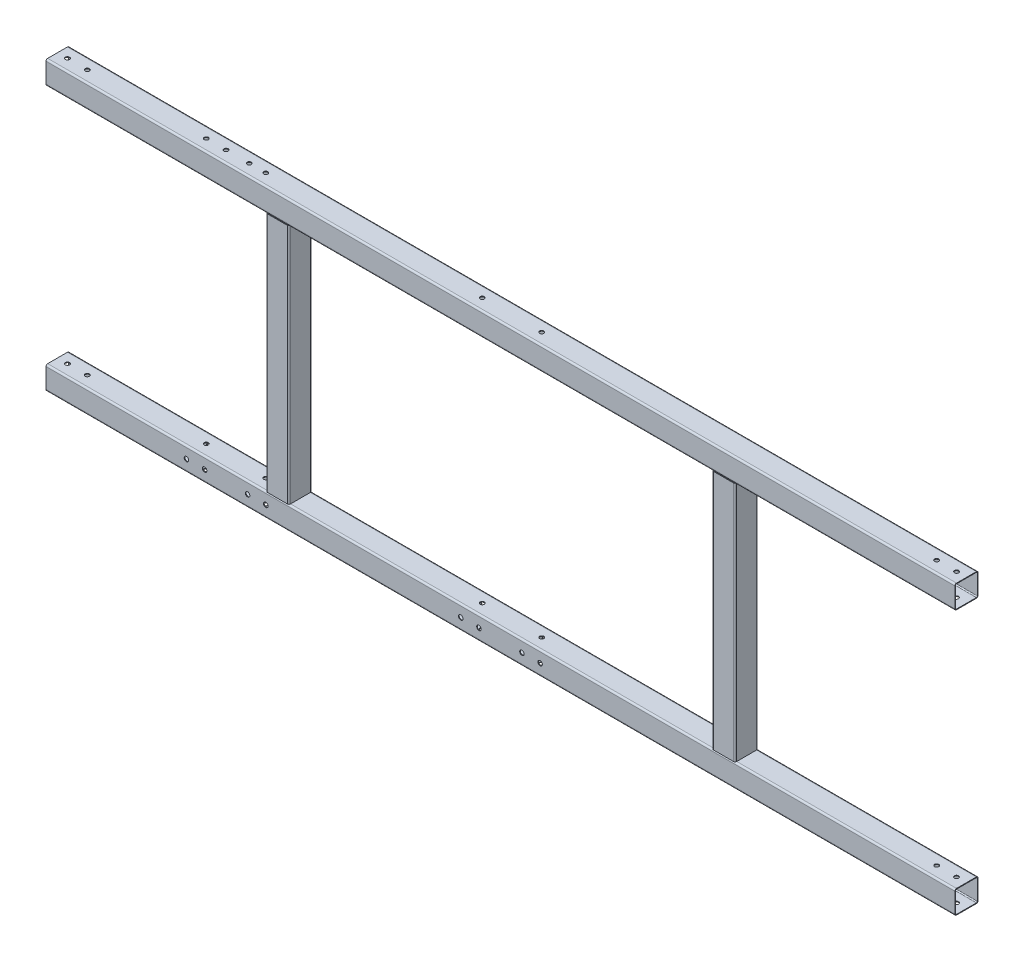
SolidWorks part; units mm, degrees
ref_plane "Alzado" through (0, 0, 0) normal (0, 0, 1) x (1, 0, 0)
ref_plane "Planta" through (0, 0, 0) normal (0, 1, 0) x (1, 0, 0)
ref_plane "Vista lateral" through (0, 0, 0) normal (1, 0, 0) x (0, 0, -1)
sketch "Croquis1" plane through (0, 0, 0) normal (0, 0, 1) x (1, 0, 0)
  line L0 (-675, 400) -> (-675, -400)
  line L1 (1375, -400) -> (-1375, -400)
  line L2 (1375, -400) -> (1375, 400) construction
  line L3 (1375, 400) -> (-1375, 400)
  line L4 (-1375, -400) -> (-1375, 400) construction
  line L5 (1375, -400) -> (-1375, 400) construction
  line L6 (1375, 400) -> (-1375, -400) construction
  line L7 (675, 400) -> (675, -400)
  point P0 (0, 0)
  dimension "D1" = 800
  dimension "D2" = 2750
  dimension "D3" = 700
  dimension "D4" = 700
other "Tubo cuadrado 3 X 3 X 0.25(1)"
ref_plane "Plano1" through (1375, -400, 0) normal (-1, 0, 0) x (0, -1, 0)
sketch "Sketch1" plane through (1375, -400, 0) normal (-1, 0, 0) x (0, -1, 0)
  line L0 (-30, -33) -> (30, -33)
  line L1 (-33, -30) -> (-33, 30)
  line L2 (30, 33) -> (-30, 33)
  line L3 (33, 30) -> (33, -30)
  line L4 (-30, -35) -> (30, -35)
  line L5 (-35, -30) -> (-35, 30)
  line L6 (30, 35) -> (-30, 35)
  line L7 (35, 30) -> (35, -30)
  line L8 (0, 0) -> (33, 0) construction
  line L9 (0, 0) -> (0, 33) construction
  arc A0 (35, 30) -> (30, 35) centre (30, 30) ccw
  arc A1 (30, -35) -> (35, -30) centre (30, -30) ccw
  arc A2 (-35, -30) -> (-30, -35) centre (-30, -30) ccw
  arc A3 (-30, 35) -> (-35, 30) centre (-30, 30) ccw
  arc A4 (-30, 33) -> (-33, 30) centre (-30, 30) ccw
  arc A5 (33, 30) -> (30, 33) centre (30, 30) ccw
  arc A6 (30, -33) -> (33, -30) centre (30, -30) ccw
  arc A7 (-33, -30) -> (-30, -33) centre (-30, -30) ccw
  point P3 (0, 35)
  point P4 (35, 0)
  point P5 (0, -35)
  point P6 (-35, 0)
  point P7 (-35, 35)
  point P8 (-35, -35)
  point P33 (0, 0)
  point P35 (35, -35)
  point P36 (35, 35)
  point P37 (0, 0)
  dimension "D1" = 5
  dimension "Thickness" = 2
  dimension "V_leg" = 70
sketch "Croquis4" plane through (0, 435, 0) normal (0, 1, 0) x (1, 0, 0)
  line L0 (-1375, 0) -> (1375, 0) construction
  line L1 (-1375, -30) -> (-1375, 30) construction
  line L2 (1375, -30) -> (1375, 30) construction
  line L3 (0, 0) -> (0, 145.7469) construction
  line L4 (-1375, 30) -> (-1375, -30) construction
  circle A0 centre (-1345, 0) radius 6.35
  circle A1 centre (-1285, 0) radius 6.35
  circle A2 centre (1285, 0) radius 6.35
  circle A3 centre (1345, 0) radius 6.35
  circle A4 centre (-925, 0) radius 6.35
  circle A5 centre (-745, 0) radius 6.35
  circle A6 centre (-90, 0) radius 6.35
  circle A7 centre (90, 0) radius 6.35
  dimension "D1" = 12.7
  dimension "D2" = 12.7
  dimension "D4" = 60
  dimension "D5" = 12.7
  dimension "D6" = 12.7
  dimension "D7" = 180
  dimension "D8" = 450
  dimension "D9" = 12.7
  dimension "D10" = 12.7
  dimension "D11" = 180
  dimension "D12" = 1285
  dimension "D3" = 30
extrude "Cortar-Extruir1" cut sketch "Croquis4" against normal through all
sketch "Croquis5" plane through (0, 0, -35) normal (0, 0, -1) x (-1, 0, 0)
  line L0 (-155.1213, -400) -> (177.5561, -400) construction
  line L1 (-1375, -370) -> (-1375, -430) construction
  line L2 (674.8787, -400) -> (1007.5561, -400) construction
  circle A0 centre (-120, -400) radius 6.8348
  circle A1 centre (-65, -400) radius 6.8348
  circle A2 centre (65, -400) radius 6.8348
  circle A3 centre (120, -400) radius 6.8348
  circle A4 centre (710, -400) radius 6.8348
  circle A5 centre (765, -400) radius 6.8348
  circle A6 centre (895, -400) radius 6.8348
  circle A7 centre (950, -400) radius 6.8348
  dimension "D1" = 55
  dimension "D2" = 1255
  dimension "D3" = 55
  dimension "D4" = 130
  dimension "D5" = 2
extrude "Cortar-Extruir2" cut sketch "Croquis5" against normal through all
sketch "Croquis6" plane through (0, 435, 0) normal (0, 1, 0) x (1, 0, 0)
  line L0 (-1375, 0) -> (-401.8692, 0) construction
  line L1 (-1375, -30) -> (-1375, 30) construction
  circle A0 centre (-865, 0) radius 6.35
  circle A1 centre (-795, 0) radius 6.35
  dimension "D1" = 12.7
  dimension "D2" = 12.7
  dimension "D3" = 70
  dimension "D4" = 510
extrude "Cortar-Extruir3" cut sketch "Croquis6" against normal blind 160
